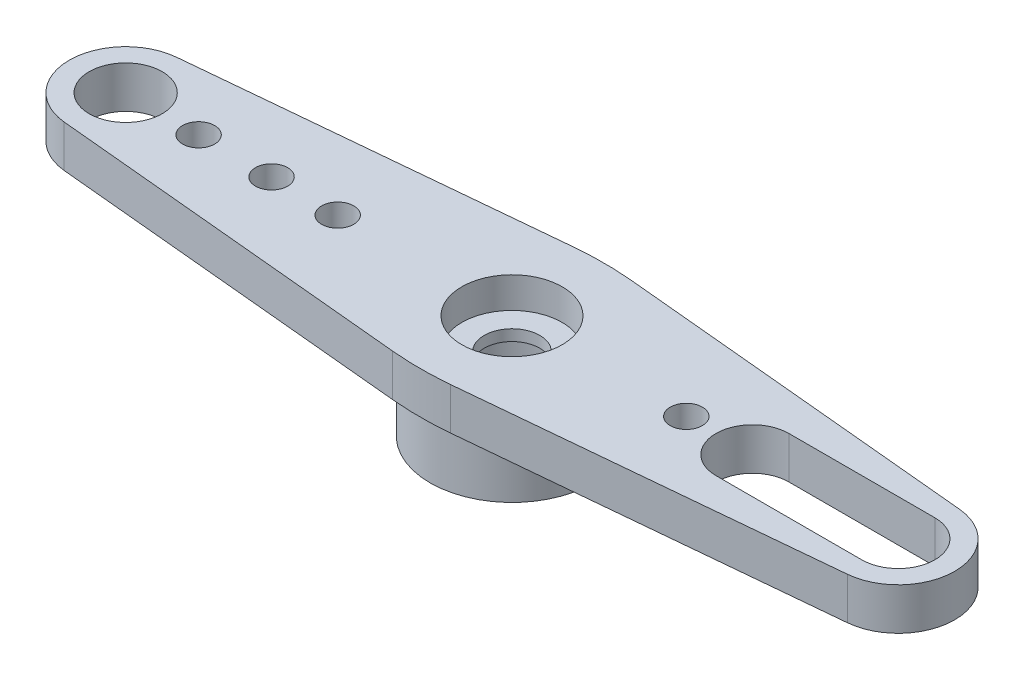
SolidWorks part; units mm, degrees
ref_plane "Front Plane" through (0, 0, 0) normal (0, 0, 1) x (1, 0, 0)
ref_plane "Top Plane" through (0, 0, 0) normal (0, 1, 0) x (1, 0, 0)
ref_plane "Right Plane" through (0, 0, 0) normal (1, 0, 0) x (0, 0, -1)
sketch "Sketch1" plane through (0, 0, 0) normal (0, 1, 0) x (1, 0, 0)
  circle A0 centre (0, 0) radius 3.3655
  circle A1 centre (0, 0) radius 2.5
  dimension "D1" = 6.731
  dimension "D2" = 5
extrude "Boss-Extrude1" add sketch "Sketch1" along normal blind 2.54
sketch "Sketch2" plane through (0, 2.54, 0) normal (0, 1, 0) x (1, 0, 0)
  line L0 (-1000, 0) -> (9.8806, 0) construction
  line L1 (0, 0) -> (0, 50000) construction
  line L2 (0, 3.8227) -> (16.0923, 2.3075)
  line L3 (0, -3.8227) -> (16.0923, -2.3075)
  line L4 (0, -3.8227) -> (-16.0923, -2.3075)
  line L5 (0, 3.8227) -> (-16.0923, 2.3075)
  line L6 (15.875, 0) -> (9.8806, 0) construction
  line L7 (15.875, -1.5) -> (9.8806, -1.5)
  line L8 (15.875, 1.5) -> (9.8806, 1.5)
  line L9 (15.875, 0) -> (50000, 0) construction
  arc A0 (15.875, -1.5) -> (15.875, 1.5) centre (15.875, 0) ccw
  arc A2 (9.8806, 1.5) -> (9.8806, -1.5) centre (9.8806, 0) ccw
  circle A3 centre (7.1628, 0) radius 0.6604
  arc A4 (14.1081, -1.5) -> (14.1081, 1.5) centre (15.875, 0) ccw
  circle A5 centre (0, 0) radius 3.8227
  circle A6 centre (-15.875, 0) radius 2.3178
  circle A7 centre (-7.1628, 0) radius 0.6604
  circle A8 centre (-9.8806, 0) radius 0.6604
  circle A9 centre (-12.8778, 0) radius 0.6604
  circle A10 centre (-15.875, 0) radius 1.5
  circle A11 centre (0, 0) radius 1.143
  arc A12 (15.875, -1.5) -> (15.875, 1.5) centre (15.875, 0) ccw
  arc A13 (9.8806, 1.5) -> (9.8806, -1.5) centre (9.8806, 0) ccw
  point P33 (12.8778, 0)
  dimension "D1" = 3
  dimension "D6" = 4.6355
  dimension "D7" = 7.6454
  dimension "D8" = 2.286
  dimension "D9" = 3
  dimension "D2" = 15.875
  dimension "D4" = 5.9944
  dimension "D5" = 8.7122
extrude "Boss-Extrude2" add sketch "Sketch2" along normal blind 1.7272
fillet "Fillet1" radius 12.7 2 edges at (0, 3.4036, -3.8227) (0, 3.4036, 3.8227)
sketch "Sketch3" plane through (0, 4.2672, 0) normal (0, 1, 0) x (1, 0, 0)
  circle A0 centre (0, 0) radius 2.0638
  circle M17 centre (0, 0) radius 1.143
  dimension "D1" = 4.1275
extrude "Cut-Extrude1" cut sketch "Sketch3" against normal blind 1.27 contours A0 M17
